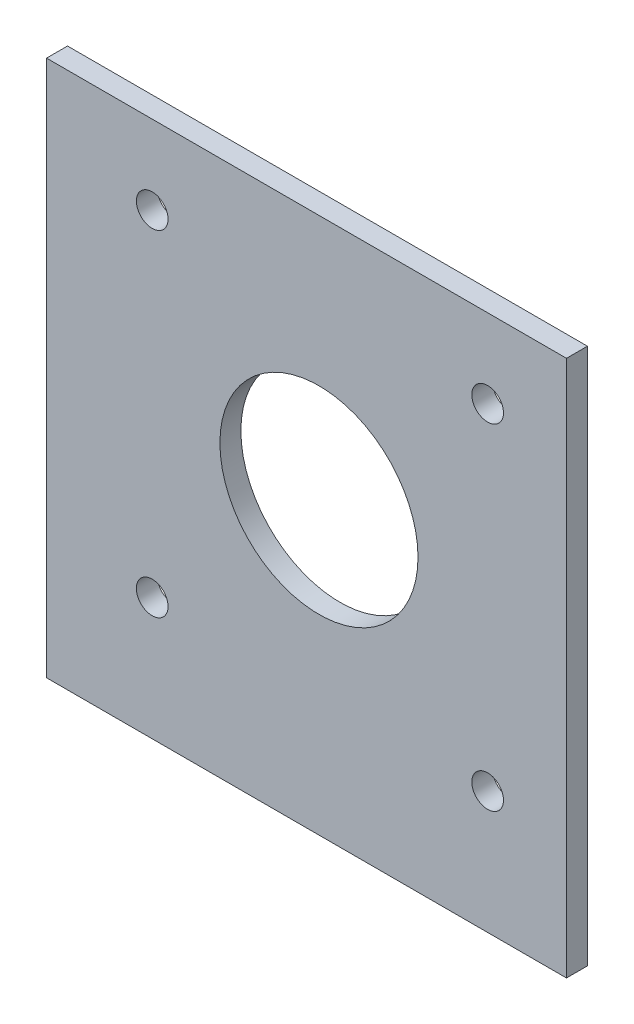
SolidWorks part; units mm, degrees
material "AISI 4130 Steel, annealed at 865C"
ref_plane "X-Y Datum" through (0, 0, 0) normal (0, 0, 1) x (1, 0, 0)
ref_plane "X-Z Datum" through (0, 0, 0) normal (0, 1, 0) x (1, 0, 0)
ref_plane "Y-Z Datum" through (0, 0, 0) normal (1, 0, 0) x (0, 0, -1)
sketch "Sketch2" plane through (0, 0, 0) normal (0, 0, 1) x (1, 0, 0)
  line L0 (34.29, 38.1) -> (-34.29, 38.1)
  line L2 (-34.29, 38.1) -> (-34.29, -38.1)
  line L4 (-34.29, 38.1) -> (0, 0) construction
  line L5 (-34.29, -38.1) -> (0, 0) construction
  line L6 (-34.29, -38.1) -> (34.29, -38.1)
  line L7 (34.29, -38.1) -> (34.29, 38.1)
  line L8 (0, 0) -> (34.29, -38.1) construction
  line L9 (0, 0) -> (34.29, 38.1) construction
  dimension "D1" = 68.58
  dimension "D3" = 76.2
extrude "Boss-Extrude1" add sketch "Sketch2" along normal mid plane 3.175
hole_wizard "M4 Clearance Hole1" positions "Sketch3" profile "Sketch4" hole size "M4" standard "ANSI Metric" end condition up to next
sketch "Sketch3" plane through (0, 0, 1.5875) normal (0, 0, 1) x (1, 0, 0)
  point P0 (-23.368, -19.558)
  point P3 (-23.368, 31.242)
  point P6 (27.432, 31.242)
  point P9 (27.432, -19.558)
sketch "Sketch4" plane through (-23.368, -19.558, 1.5875) normal (1, 0, 0) x (0, -1, 0)
  line L0 (0, 0) -> (0, 3.175)
  line L1 (0, 3.175) -> (2.4, 3.175)
  line L2 (2.4, 3.175) -> (2.4, 0)
  line L5 (2.4, 0) -> (0, 0)
  line L11 (0, -6.35) -> (0, 107.95) construction
  dimension "Thru Hole Dia." = 4.8
  dimension "Thru Hole Depth" = 3.175
sketch "Sketch5" plane through (0, 0, 1.5875) normal (0, 0, 1) x (1, 0, 0)
  circle A0 centre (1.884, 5.842) radius 15 construction
  circle A1 centre (1.884, 5.842) radius 15
  dimension "D1" = 30
extrude "Cut-Extrude1" cut sketch "Sketch5" against normal through all
sketch "Sketch6" plane through (0, 0, -1.5875) normal (0, 0, -1) x (-1, 0, 0)
  line L0 (-34.29, -38.1) -> (-39.37, -38.1) construction
  line L1 (34.29, 38.1) -> (39.37, 38.1) construction
  line L2 (39.37, 38.1) -> (39.37, 43.18) construction
  line L3 (23.368, -21.958) -> (23.368, -27.038) construction
  line L4 (-39.37, -38.1) -> (39.37, -38.1)
  line L5 (-39.37, -38.1) -> (-39.37, 43.18)
  line L6 (-39.37, 43.18) -> (39.37, 43.18)
  line L7 (39.37, -38.1) -> (39.37, 43.18)
  line L8 (-34.29, -38.1) -> (34.29, -38.1)
  line L9 (-34.29, -38.1) -> (-34.29, 38.1)
  line L10 (-34.29, 38.1) -> (34.29, 38.1)
  line L11 (34.29, -38.1) -> (34.29, 38.1)
  line L12 (23.368, -27.038) -> (39.37, -27.038) construction
  line L13 (39.37, -27.038) -> (-58.3715, -144.7504) construction
  circle A0 centre (23.368, -19.558) radius 2.4 construction
  line M7 (-34.29, 38.1) -> (-34.29, -38.1)
  line M9 (34.29, -38.1) -> (34.29, 38.1)
  line M10 (34.29, 38.1) -> (-34.29, 38.1)
extrude "Boss-Extrude2" add sketch "Sketch6" against normal through all contours L4 L7 L6 L5 M7 M10 M9
